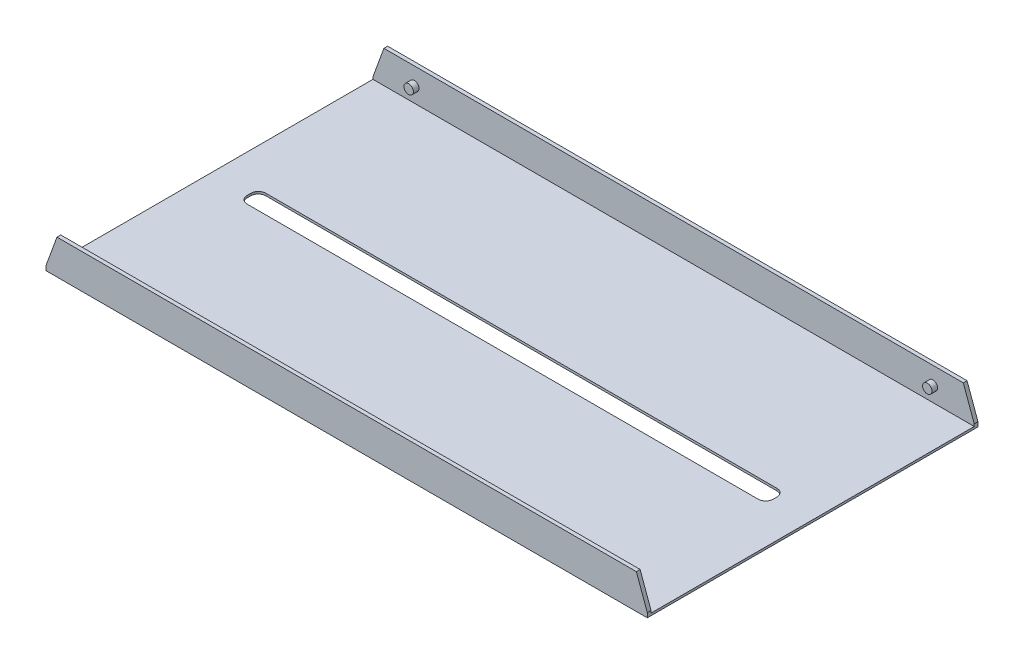
SolidWorks part; units mm, degrees
ref_plane "Front Plane" through (0, 0, 0) normal (0, 0, 1) x (1, 0, 0)
ref_plane "Top Plane" through (0, 0, 0) normal (0, 1, 0) x (1, 0, 0)
ref_plane "Right Plane" through (0, 0, 0) normal (1, 0, 0) x (0, 0, -1)
sketch "Sketch1" plane through (0, 0, 0) normal (0, 1, 0) x (1, 0, 0)
  line L1 (-80, -44) -> (80, -44)
  line L2 (-80, -44) -> (-80, 44)
  line L3 (-80, 44) -> (80, 44)
  line L4 (80, -44) -> (80, 44)
  line L5 (-80, -44) -> (80, 44) construction
  line L6 (-80, 44) -> (80, -44) construction
  point P0 (0, 0)
  dimension "D1" = 160
  dimension "D2" = 88
extrude "Boss-Extrude1" add sketch "Sketch1" along normal blind 0.6
sketch "Sketch2" plane through (0, 0.6, 0) normal (0, 1, 0) x (1, 0, 0)
  line L0 (80, -44) -> (80, 44) construction
  line L1 (-80, 44) -> (80, 44)
  line L2 (-80, 44) -> (-80, 43)
  line L3 (-80, 43) -> (80, 43)
  line L4 (80, 44) -> (80, 43)
  line L6 (80, -43) -> (-80, -43)
  line L7 (80, -43) -> (80, -44)
  line L8 (80, -44) -> (-80, -44)
  line L9 (-80, -43) -> (-80, -44)
  dimension "D1" = 1
  dimension "D2" = 1
extrude "Boss-Extrude2" add sketch "Sketch2" along normal blind 8.6
sketch "Sketch3" plane through (0, 0, -43) normal (0, 0, 1) x (1, 0, 0)
  line L0 (80, 9.2) -> (80, 0.6) construction
  line L1 (-80, 0.6) -> (80, 0.6) construction
  line L2 (-80, 9.2) -> (-80, 0.6) construction
  circle A0 centre (-69, 4.6) radius 1.25
  circle A1 centre (69, 4.6) radius 1.25
  point P6 (80, 4.9)
  point P11 (-80, 4.9)
  dimension "D1" = 2.5
  dimension "D2" = 11
  dimension "D3" = 4
  dimension "D4" = 2.5
  dimension "D5" = 11
  dimension "D6" = 4
extrude "Boss-Extrude3" add sketch "Sketch3" along normal blind 1.5
sketch "Sketch4" plane through (0, 0, 43) normal (0, 0, -1) x (-1, 0, 0)
  line L0 (80, 9.2) -> (80, 0.6) construction
  line L1 (-80, 0.6) -> (80, 0.6) construction
  line L2 (-80, 9.2) -> (-80, 0.6) construction
  circle A0 centre (-69, 4.6) radius 1.25
  circle A1 centre (69, 4.6) radius 1.25
  point P10 (-80, 4.9)
  dimension "D1" = 2.5
  dimension "D2" = 11
  dimension "D3" = 4
  dimension "D4" = 2.5
  dimension "D5" = 11
  dimension "D6" = 4
extrude "Boss-Extrude4" add sketch "Sketch4" along normal blind 1.5
chamfer "Chamfer1" distance 8 angle 20 4 edges at (-80, 9.2, 43.5) (-80, 9.2, -43.5) (80, 9.2, -43.5) (80, 9.2, 43.5)
sketch "Sketch5" plane through (0, 0.6, 0) normal (0, 1, 0) x (1, 0, 0)
  line L1 (-70, 2.5) -> (70, 2.5)
  line L2 (-70, 2.5) -> (-70, -2.5)
  line L3 (-70, -2.5) -> (70, -2.5)
  line L4 (70, 2.5) -> (70, -2.5)
  line L5 (-70, 2.5) -> (70, -2.5) construction
  line L6 (-70, -2.5) -> (70, 2.5) construction
  point P0 (0, 0)
  dimension "D1" = 5
  dimension "D2" = 140
extrude "Cut-Extrude1" cut sketch "Sketch5" against normal blind 1.5
fillet "Fillet1" radius 2 4 edges at (-70, 0.3, -2.5) (-70, 0.3, 2.5) (70, 0.3, 2.5) (70, 0.3, -2.5)
